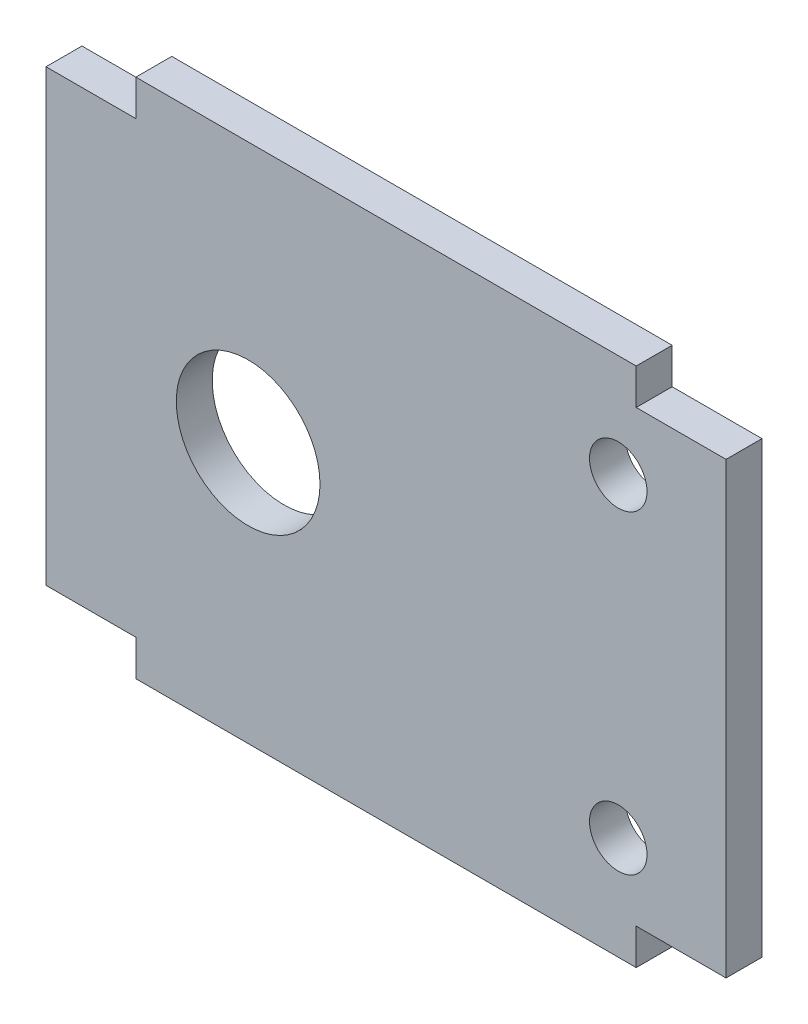
SolidWorks part; units mm, degrees
ref_plane "Ön Düzlem" through (0, 0, 0) normal (0, 0, 1) x (1, 0, 0)
ref_plane "Üst Düzlem" through (0, 0, 0) normal (0, 1, 0) x (1, 0, 0)
ref_plane "Sağ Düzlem" through (0, 0, 0) normal (1, 0, 0) x (0, 0, -1)
sketch "Çizim1" plane through (0, 0, 0) normal (0, 0, 1) x (1, 0, 0)
  line L0 (0, 0) -> (20.6, 0) construction
  line L1 (20.6, 8.75) -> (20.6, -8.75) construction
  line L2 (-11.25, 12.5) -> (-11.25, -12.5)
  line L3 (-11.25, -12.5) -> (26.6, -12.5)
  line L4 (26.6, -12.5) -> (26.6, 12.5)
  line L5 (-11.25, 12.5) -> (26.6, 12.5)
  circle A1 centre (20.6, -8.75) radius 1.6
  circle A2 centre (20.6, 8.75) radius 1.6
  circle A4 centre (0, 0) radius 4
  point P14 (26.6, 0)
  point P15 (-11.25, 0)
  dimension "D2" = 3.2
  dimension "D4" = 8
  dimension "D1" = 17.5
  dimension "D3" = 20.6
  dimension "D5" = 11.25
  dimension "D6" = 12.5
  dimension "D7" = 6
extrude "Yükseklik-Ekstrüzyon1" add sketch "Çizim1" along normal blind 2
sketch "Çizim2" plane through (0, -12.5, 0) normal (0, -1, 0) x (1, 0, 0)
  line L0 (-11.25, 2) -> (26.6, 2) construction
  line L1 (-6.25, 2) -> (21.6, 2)
  line L2 (-6.25, 2) -> (-6.25, 0)
  line L3 (-6.25, 0) -> (21.6, 0)
  line L4 (21.6, 2) -> (21.6, 0)
  line L5 (-11.25, 0) -> (26.6, 0) construction
  line L6 (-11.25, 2) -> (-11.25, 0) construction
  line L7 (26.6, 2) -> (26.6, 0) construction
  dimension "D1" = 5
  dimension "D2" = 5
extrude "Yükseklik-Ekstrüzyon2" add sketch "Çizim2" along normal blind 2
mirror "Aynalama1" about plane through (0, 0, 0) normal (0, 1, 0) of "Yükseklik-Ekstrüzyon2"
